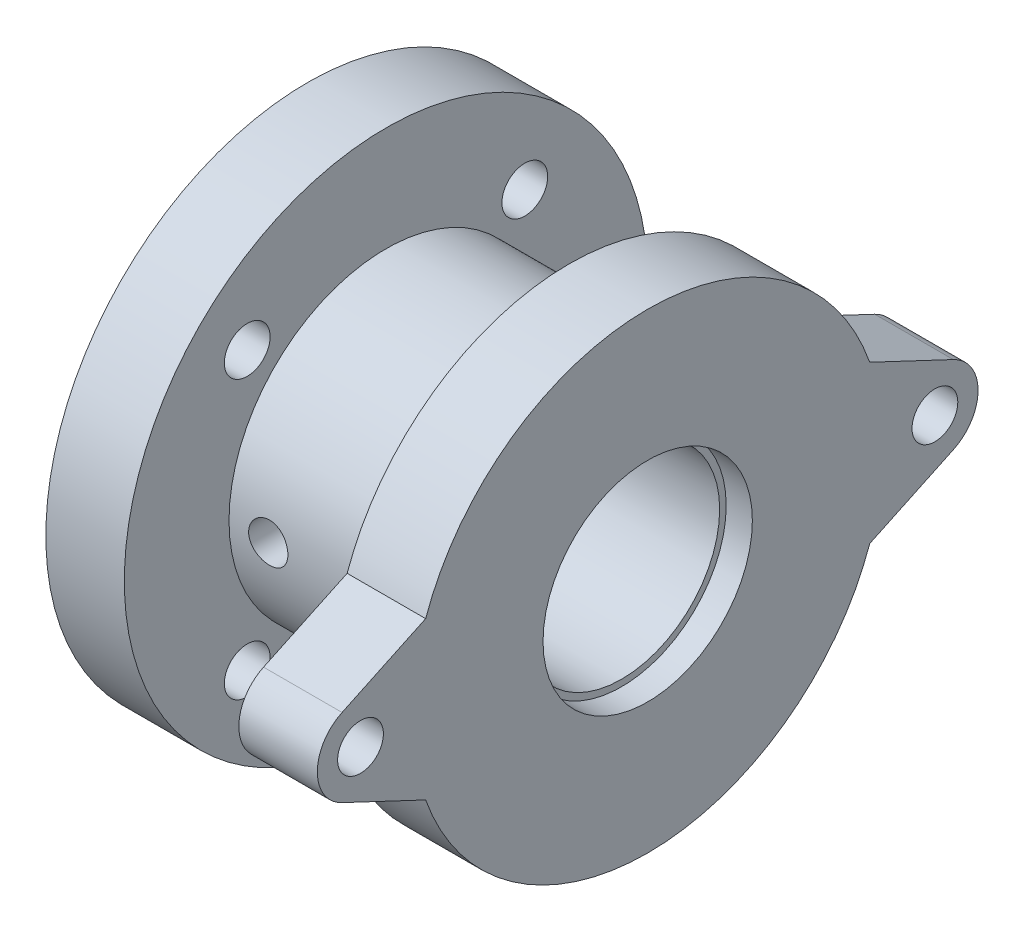
SolidWorks part; units mm, degrees
ref_plane "Front Plane" through (0, 0, 0) normal (0, 0, 1) x (1, 0, 0)
ref_plane "Top Plane" through (0, 0, 0) normal (0, 1, 0) x (1, 0, 0)
ref_plane "Right Plane" through (0, 0, 0) normal (1, 0, 0) x (0, 0, -1)
sketch "Sketch1" plane through (0, 0, 0) normal (1, 0, 0) x (0, 0, -1)
  circle A0 centre (0, 0) radius 20
  circle A1 centre (0, 0) radius 7.5
  dimension "D1" = 40
  dimension "D2" = 15
extrude "Boss-Extrude1" add sketch "Sketch1" along normal blind 6
sketch "Sketch3" plane through (6, 0, 0) normal (1, 0, 0) x (0, 0, -1)
  circle A0 centre (0, 0) radius 7.5
  circle A1 centre (0, 0) radius 12
  circle A2 centre (0, 0) radius 7.5 construction
  dimension "D1" = 24
extrude "Boss-Extrude2" add sketch "Sketch3" along normal blind 14
sketch "Sketch4" plane through (0, 0, 0) normal (0, 0, 1) x (1, 0, 0)
  circle A0 centre (9, 0) radius 1.5
  dimension "D1" = 3
  dimension "D2" = 9
extrude "Cut-Extrude2" cut sketch "Sketch4" against normal through all both and the other way through all
sketch "Sketch5" plane through (20, 0, 0) normal (1, 0, 0) x (0, 0, -1)
  circle A0 centre (0, 0) radius 7.5
  circle A1 centre (0, 0) radius 7.5 construction
  circle A2 centre (0, 0) radius 18
  dimension "D1" = 36
extrude "Boss-Extrude3" add sketch "Sketch5" along normal blind 6
sketch "Sketch6" plane through (26, 0, 0) normal (1, 0, 0) x (0, 0, -1)
  line L0 (-21.95, 0) -> (21.95, 0) construction
  line L1 (-23.3588, 2.9842) -> (-16.9706, 6)
  line L2 (-23.3588, -2.9842) -> (-16.9706, -6)
  line L3 (23.3588, 2.9842) -> (16.9706, 6)
  line L4 (23.3588, -2.9842) -> (16.9706, -6)
  line L5 (-25.25, 0) -> (25.25, 0) construction
  circle A0 centre (-21.95, 0) radius 1.75
  circle A1 centre (21.95, 0) radius 1.75
  arc A2 (-23.3588, 2.9842) -> (-23.3588, -2.9842) centre (-21.95, 0) ccw
  arc A3 (23.3588, -2.9842) -> (23.3588, 2.9842) centre (21.95, 0) ccw
  arc A4 (-16.9706, 6) -> (-16.9706, -6) centre (0, 0) ccw
  circle A5 centre (0, 0) radius 18 construction
  arc A6 (16.9706, -6) -> (16.9706, 6) centre (0, 0) ccw
  point P3 (0, 0)
  point P17 (18, 0)
  point P18 (0, 0)
  point P20 (-18, 0)
  dimension "D2" = 3.5
  dimension "D3" = 3.5
  dimension "D1" = 43.9
  dimension "D4" = 12
  dimension "D5" = 50.5
extrude "Boss-Extrude4" add sketch "Sketch6" against normal up to surface (6 mm away) up to face at (20, 0, -12)
sketch "Sketch2" plane through (0, 0, 0) normal (-1, 0, 0) x (0, 0, 1)
  line L0 (0, 0) -> (0, 13.5213) construction
  line L1 (0, 0) -> (-10.6066, 10.6066) construction
  circle A0 centre (-10.6066, 10.6066) radius 1.75
  circle A1 centre (10.6066, 10.6066) radius 1.75
  circle A2 centre (10.6066, -10.6066) radius 1.75
  circle A3 centre (-10.6066, -10.6066) radius 1.75
  point P14 (0, 0)
  dimension "D3" = 3.5
  dimension "D1" = 15
  dimension "D2" = 45
  dimension "D4" = 4
extrude "Cut-Extrude1" cut sketch "Sketch2" against normal up to surface (6 mm away) up to face at (6, 0, -20)
sketch "Sketch7" plane through (26, 0, 0) normal (1, 0, 0) x (0, 0, -1)
  circle A0 centre (0, 0) radius 8
  dimension "D1" = 16
extrude "Cut-Extrude3" cut sketch "Sketch7" against normal blind 2
